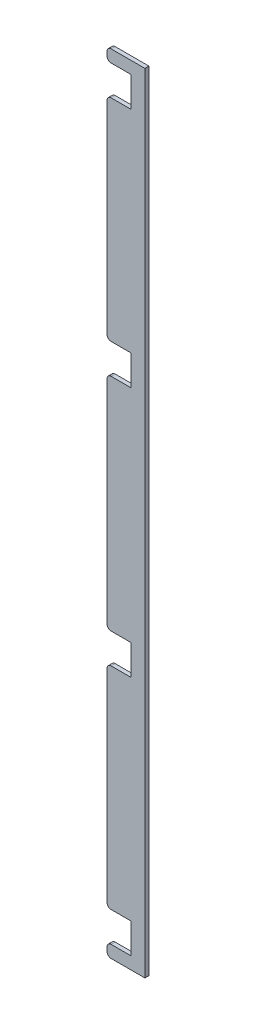
SolidWorks part; units mm, degrees
ref_plane "Front Plane" through (0, 0, 0) normal (0, 0, 1) x (1, 0, 0)
ref_plane "Top Plane" through (0, 0, 0) normal (0, 1, 0) x (1, 0, 0)
ref_plane "Right Plane" through (0, 0, 0) normal (1, 0, 0) x (0, 0, -1)
sketch "Sketch1" plane through (0, 0, 0) normal (0, 0, 1) x (1, 0, 0)
  line L0 (0, -182.5952) -> (-4.5, -182.5952)
  line L2 (0, 13.4048) -> (0, -182.5952)
  line L6 (-4.5, 10.3548) -> (-3.5, 10.3548)
  line L7 (-3.5, 10.3548) -> (-3.5, 2.8548)
  line L8 (0, 2.4048) -> (0, -5.5952) construction
  line L9 (-3.5, 2.8548) -> (-4.5, 2.8548)
  line L10 (-4.5, -49.6452) -> (-3.5, -49.6452)
  line L11 (-3.5, -49.6452) -> (-3.5, -57.1452)
  line L12 (-3.5, -57.1452) -> (-4.5, -57.1452)
  line L13 (-4.5, -112.0452) -> (-3.5, -112.0452)
  line L14 (-3.5, -112.0452) -> (-3.5, -119.5452)
  line L15 (-3.5, -119.5452) -> (-4.5, -119.5452)
  line L16 (-4.5, -172.0452) -> (-3.5, -172.0452)
  line L17 (-3.5, -172.0452) -> (-3.5, -179.5452)
  line L18 (-3.5, -179.5452) -> (-4.5, -179.5452)
  line L100 (-8.4, 10.3548) -> (-4.5, 10.3548)
  line L101 (-4.5, 10.3548) -> (-4.5, 2.8548)
  line L102 (-4.5, 2.8548) -> (-8.4, 2.8548)
  line L103 (-9.4, 1.8548) -> (-9.4, -48.6452)
  line L104 (-8.4, -49.6452) -> (-4.5, -49.6452)
  line L105 (-4.5, -49.6452) -> (-4.5, -57.1452)
  line L106 (-4.5, -57.1452) -> (-8.4, -57.1452)
  line L107 (-9.4, -58.1452) -> (-9.4, -111.0452)
  line L108 (-8.4, -112.0452) -> (-4.5, -112.0452)
  line L109 (-4.5, -112.0452) -> (-4.5, -119.5452)
  line L110 (-4.5, -119.5452) -> (-8.4, -119.5452)
  line L111 (-9.4, -120.5452) -> (-9.4, -171.0452)
  line L112 (-8.4, -172.0452) -> (-4.5, -172.0452)
  line L113 (-4.5, -172.0452) -> (-4.5, -179.5452)
  line L114 (-4.5, -179.5452) -> (-8.4, -179.5452)
  line L115 (-9.4, -180.5452) -> (-9.4, -181.5952)
  line L116 (-8.4, -182.5952) -> (-4.5, -182.5952)
  line L117 (-4.5, -182.5952) -> (-4.5, -191.5952)
  line L118 (-4.5, -191.5952) -> (78.5, -191.5952)
  line L119 (78.5, -191.5952) -> (78.5, -182.5952)
  line L120 (78.5, -182.5952) -> (82.4, -182.5952)
  line L121 (83.4, -181.5952) -> (83.4, -180.5452)
  line L122 (82.4, -179.5452) -> (78.5, -179.5452)
  line L123 (78.5, -179.5452) -> (78.5, -172.0452)
  line L124 (78.5, -172.0452) -> (82.4, -172.0452)
  line L125 (83.4, -171.0452) -> (83.4, -120.5452)
  line L126 (82.4, -119.5452) -> (78.5, -119.5452)
  line L127 (78.5, -119.5452) -> (78.5, -112.0452)
  line L128 (78.5, -112.0452) -> (82.4, -112.0452)
  line L129 (83.4, -111.0452) -> (83.4, -58.1452)
  line L130 (82.4, -57.1452) -> (78.5, -57.1452)
  line L131 (78.5, -57.1452) -> (78.5, -49.6452)
  line L132 (78.5, -49.6452) -> (82.4, -49.6452)
  line L133 (83.4, -48.6452) -> (83.4, 1.8548)
  line L134 (82.4, 2.8548) -> (78.5, 2.8548)
  line L135 (78.5, 2.8548) -> (78.5, 10.3548)
  line L136 (78.5, 10.3548) -> (82.4, 10.3548)
  line L137 (83.4, 11.3548) -> (83.4, 12.4048)
  line L138 (82.4, 13.4048) -> (78.5, 13.4048)
  line L139 (78.5, 13.4048) -> (78.5, 22.4048)
  line L140 (78.5, 22.4048) -> (-4.5, 22.4048)
  line L141 (-4.5, 22.4048) -> (-4.5, 13.4048)
  line L142 (-4.5, 13.4048) -> (-8.4, 13.4048)
  line L143 (-9.4, 12.4048) -> (-9.4, 11.3548)
  line L144 (-8.4, 10.3548) -> (-4.5, 10.3548)
  line L145 (-4.5, 10.3548) -> (-4.5, 2.8548)
  line L146 (-4.5, 2.8548) -> (-8.4, 2.8548)
  line L147 (-9.4, 1.8548) -> (-9.4, -48.6452)
  line L148 (-8.4, -49.6452) -> (-4.5, -49.6452)
  line L149 (-4.5, -49.6452) -> (-4.5, -57.1452)
  line L150 (-4.5, -57.1452) -> (-8.4, -57.1452)
  line L151 (-9.4, -58.1452) -> (-9.4, -111.0452)
  line L152 (-8.4, -112.0452) -> (-4.5, -112.0452)
  line L153 (-4.5, -112.0452) -> (-4.5, -119.5452)
  line L154 (-4.5, -119.5452) -> (-8.4, -119.5452)
  line L155 (-9.4, -120.5452) -> (-9.4, -171.0452)
  line L156 (-8.4, -172.0452) -> (-4.5, -172.0452)
  line L157 (-4.5, -172.0452) -> (-4.5, -179.5452)
  line L158 (-4.5, -179.5452) -> (-8.4, -179.5452)
  line L159 (-9.4, -180.5452) -> (-9.4, -181.5952)
  line L160 (-8.4, -182.5952) -> (-4.5, -182.5952)
  line L186 (0, 13.4048) -> (-8.4, 13.4048)
  line L187 (-9.4, 12.4048) -> (-9.4, 11.3548)
  arc A40 (-8.4, 2.8548) -> (-9.4, 1.8548) centre (-8.4, 1.8548) ccw
  arc A41 (-9.4, -48.6452) -> (-8.4, -49.6452) centre (-8.4, -48.6452) ccw
  arc A42 (-8.4, -57.1452) -> (-9.4, -58.1452) centre (-8.4, -58.1452) ccw
  arc A43 (-9.4, -111.0452) -> (-8.4, -112.0452) centre (-8.4, -111.0452) ccw
  arc A44 (-8.4, -119.5452) -> (-9.4, -120.5452) centre (-8.4, -120.5452) ccw
  arc A45 (-9.4, -171.0452) -> (-8.4, -172.0452) centre (-8.4, -171.0452) ccw
  arc A46 (-8.4, -179.5452) -> (-9.4, -180.5452) centre (-8.4, -180.5452) ccw
  arc A47 (-9.4, -181.5952) -> (-8.4, -182.5952) centre (-8.4, -181.5952) ccw
  arc A48 (82.4, -182.5952) -> (83.4, -181.5952) centre (82.4, -181.5952) ccw
  arc A49 (83.4, -180.5452) -> (82.4, -179.5452) centre (82.4, -180.5452) ccw
  arc A50 (82.4, -172.0452) -> (83.4, -171.0452) centre (82.4, -171.0452) ccw
  arc A51 (83.4, -120.5452) -> (82.4, -119.5452) centre (82.4, -120.5452) ccw
  arc A52 (82.4, -112.0452) -> (83.4, -111.0452) centre (82.4, -111.0452) ccw
  arc A53 (83.4, -58.1452) -> (82.4, -57.1452) centre (82.4, -58.1452) ccw
  arc A54 (82.4, -49.6452) -> (83.4, -48.6452) centre (82.4, -48.6452) ccw
  arc A55 (83.4, 1.8548) -> (82.4, 2.8548) centre (82.4, 1.8548) ccw
  arc A56 (82.4, 10.3548) -> (83.4, 11.3548) centre (82.4, 11.3548) ccw
  arc A57 (83.4, 12.4048) -> (82.4, 13.4048) centre (82.4, 12.4048) ccw
  arc A58 (-8.4, 13.4048) -> (-9.4, 12.4048) centre (-8.4, 12.4048) ccw
  arc A59 (-9.4, 11.3548) -> (-8.4, 10.3548) centre (-8.4, 11.3548) ccw
  arc A60 (-8.4, 2.8548) -> (-9.4, 1.8548) centre (-8.4, 1.8548) ccw
  arc A61 (-9.4, -48.6452) -> (-8.4, -49.6452) centre (-8.4, -48.6452) ccw
  arc A62 (-8.4, -57.1452) -> (-9.4, -58.1452) centre (-8.4, -58.1452) ccw
  arc A63 (-9.4, -111.0452) -> (-8.4, -112.0452) centre (-8.4, -111.0452) ccw
  arc A64 (-8.4, -119.5452) -> (-9.4, -120.5452) centre (-8.4, -120.5452) ccw
  arc A65 (-9.4, -171.0452) -> (-8.4, -172.0452) centre (-8.4, -171.0452) ccw
  arc A66 (-8.4, -179.5452) -> (-9.4, -180.5452) centre (-8.4, -180.5452) ccw
  arc A67 (-9.4, -181.5952) -> (-8.4, -182.5952) centre (-8.4, -181.5952) ccw
  arc A78 (-8.4, 13.4048) -> (-9.4, 12.4048) centre (-8.4, 12.4048) ccw
  arc A79 (-9.4, 11.3548) -> (-8.4, 10.3548) centre (-8.4, 11.3548) ccw
  dimension "D1" = 1
  dimension "D2" = 0
extrude "Boss-Extrude1" add sketch "Sketch1" along normal blind 1
